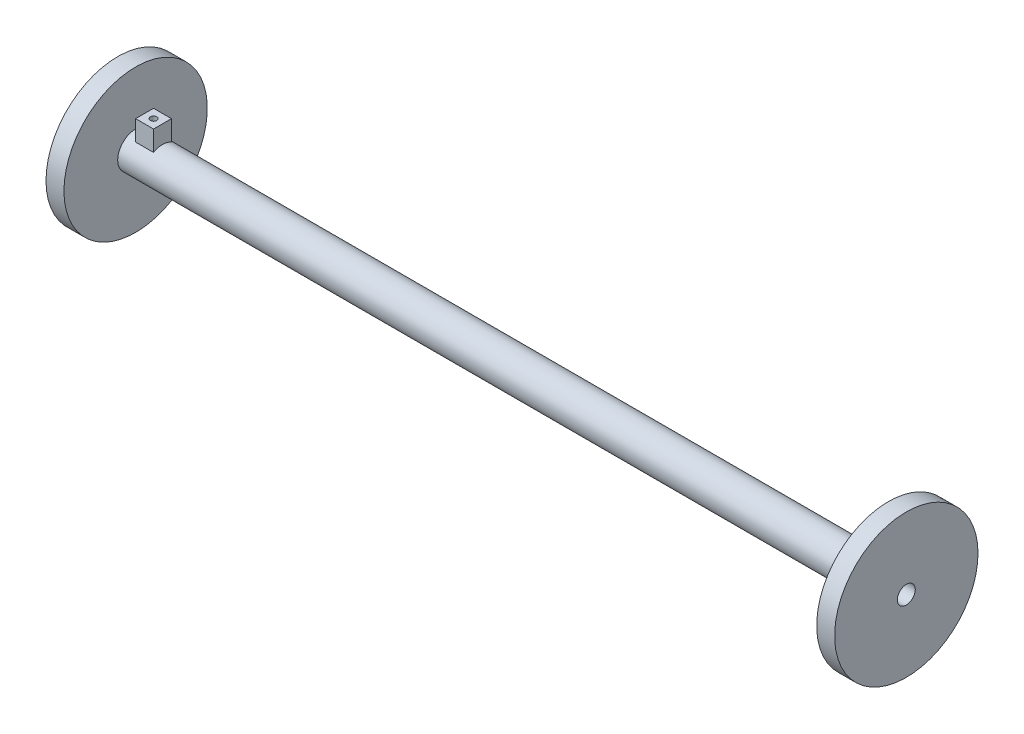
SolidWorks part; units mm, degrees
material "ABS PC"
ref_plane "Front Plane" through (0, 0, 0) normal (0, 0, 1) x (1, 0, 0)
ref_plane "Top Plane" through (0, 0, 0) normal (0, 1, 0) x (1, 0, 0)
ref_plane "Right Plane" through (0, 0, 0) normal (1, 0, 0) x (0, 0, -1)
sketch "Sketch1" plane through (0, 0, 0) normal (1, 0, 0) x (0, 0, -1)
  circle A0 centre (0, 0) radius 6.35
  circle A1 centre (0, 0) radius 12.7
  dimension "D1" = 12.7
  dimension "D2" = 25.4
extrude "Boss-Extrude1" add sketch "Sketch1" along normal mid plane 558.8
sketch "Sketch2" plane through (279.4, 0, 0) normal (1, 0, 0) x (0, 0, -1)
  circle A0 centre (0, 0) radius 6.35 construction
  circle A1 centre (0, 0) radius 6.35
  circle A2 centre (0, 0) radius 50.8
  dimension "D1" = 101.6
extrude "Boss-Extrude2" add sketch "Sketch2" against normal blind 12.7
sketch "Sketch3" plane through (-279.4, 0, 0) normal (-1, 0, 0) x (0, 0, 1)
  circle A0 centre (0, 0) radius 6.35 construction
  circle A1 centre (0, 0) radius 6.35
  circle A2 centre (0, 0) radius 50.8
  dimension "D1" = 101.6
extrude "Boss-Extrude3" add sketch "Sketch3" against normal blind 12.7
sketch "Sketch4" plane through (0, 0, 0) normal (0, 1, 0) x (1, 0, 0)
  line L0 (-279.4, 50.8) -> (-279.4, -50.8) construction
  line L1 (-260.35, -6.35) -> (-247.65, -6.35)
  line L2 (-260.35, -6.35) -> (-260.35, 6.35)
  line L3 (-260.35, 6.35) -> (-247.65, 6.35)
  line L4 (-247.65, -6.35) -> (-247.65, 6.35)
  line L5 (-260.35, -6.35) -> (-247.65, 6.35) construction
  line L6 (-260.35, 6.35) -> (-247.65, -6.35) construction
  circle A0 centre (-254, 0) radius 2.286
  point P0 (-254, 0)
  dimension "D3" = 4.572
  dimension "D1" = 25.4
  dimension "D2" = 12.7
extrude "Boss-Extrude4" add sketch "Sketch4" against normal up to next from offset 25.4
